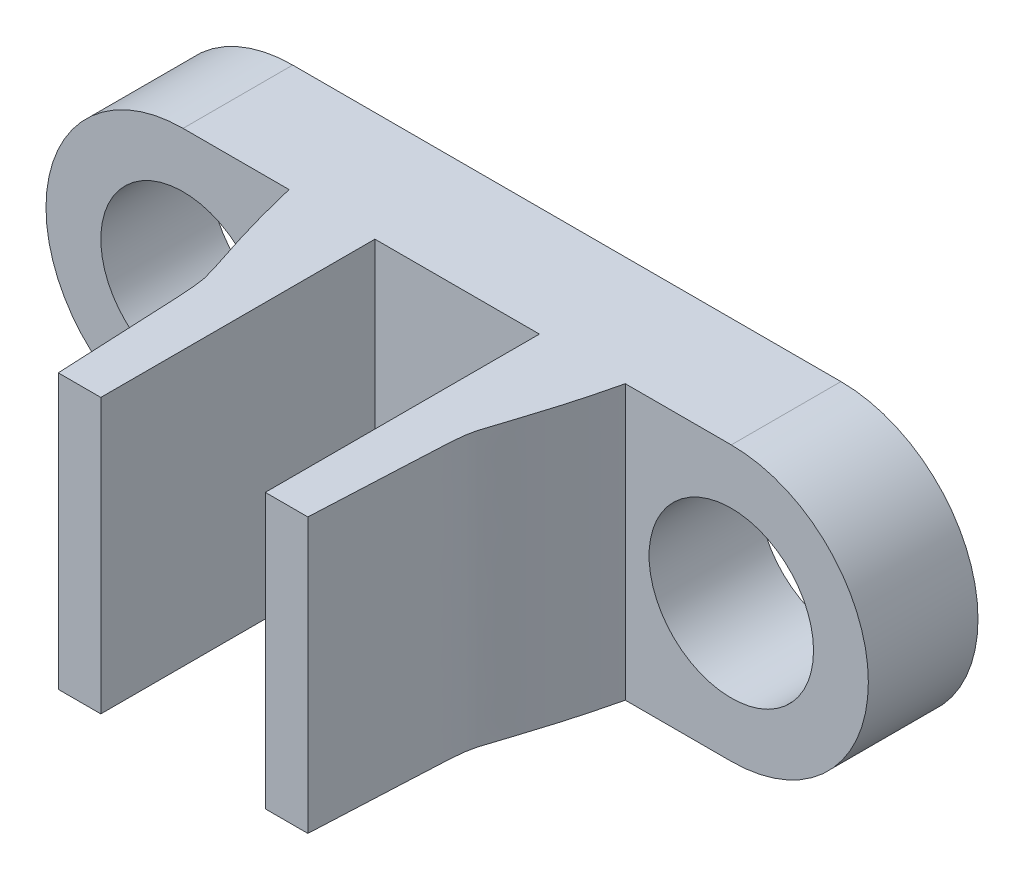
SolidWorks part; units mm, degrees
ref_plane "Front Plane" through (0, 0, 0) normal (0, 0, 1) x (1, 0, 0)
ref_plane "Top Plane" through (0, 0, 0) normal (0, 1, 0) x (1, 0, 0)
ref_plane "Right Plane" through (0, 0, 0) normal (1, 0, 0) x (0, 0, -1)
sketch "Sketch1" plane through (0, 0, 0) normal (0, 0, 1) x (1, 0, 0)
  line L0 (10, 0) -> (10, 5)
  line L1 (0, 0) -> (10, 0)
  line L2 (0, 0) -> (0, 5)
  line L3 (0, 5) -> (10, 5)
  line L4 (5, 0) -> (5, 5) construction
  circle A0 centre (0, 2.5) radius 1.5
  arc A1 (0, 5) -> (0, 0) centre (0, 2.5) ccw
  arc A2 (10, 5) -> (10, 0) centre (10, 2.5) cw
  circle A3 centre (10, 2.5) radius 1.5
  dimension "D3" = 3
  dimension "D1" = 5
  dimension "D2" = 5
extrude "Boss-Extrude1" add sketch "Sketch1" along normal blind 2 contours L1 L4 L3 L2 A0 | L4 L1 L0 A3 L3 | L0 A3 A2 | L2 A1 A0
sketch "Sketch2" plane through (0, 0, 0) normal (0, 1, 0) x (1, 0, 0)
  line L0 (0, -2) -> (10, -2) construction
  line L1 (2.7237, -2) -> (3.5, -2)
  line L2 (1.9333, -2) -> (2.7237, -2)
  line L3 (2.7237, -7) -> (3.5, -7)
  line L4 (3.5, -2) -> (3.5, -7)
  line L6 (0, -2) -> (0, 0) construction
  line L7 (5, -2) -> (5, -7.2793) construction
  line L8 (8.0667, -2) -> (7.2763, -2)
  line L9 (7.2763, -2) -> (6.5, -2)
  line L10 (6.5, -2) -> (6.5, -7)
  line L11 (7.2763, -7) -> (6.5, -7)
  spline S0 degree 3 poles (2.7237, -7) (2.6235, -5.0965) (2.6268, -4.3778) (2.4339, -3.7138) (2.1764, -3.0276) (1.9333, -2) knots 0 0 0 0 0.370676 0.470676 1 1 1 1
  spline S1 degree 3 poles (7.2763, -7) (7.3765, -5.0965) (7.3732, -4.3778) (7.5661, -3.7138) (7.8236, -3.0276) (8.0667, -2) knots 0 0 0 0 0.370676 0.470676 1 1 1 1
  point P8 (3.1119, -7)
  dimension "D1" = 3.1119
  dimension "D2" = 1.5
  dimension "D3" = 5
extrude "Boss-Extrude2" add sketch "Sketch2" along normal blind 5
